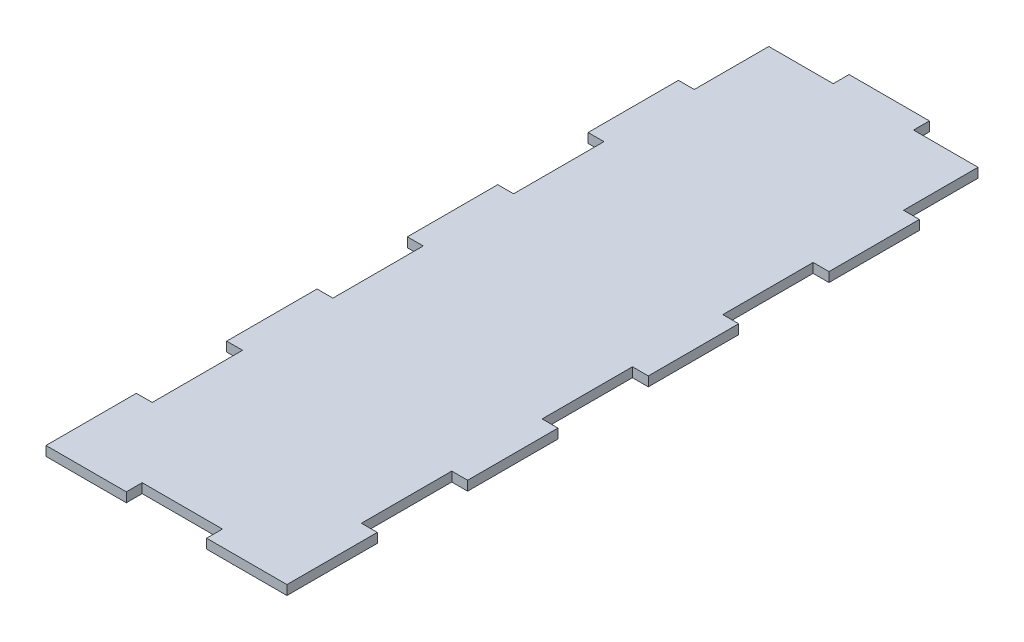
SolidWorks part; units mm, degrees
ref_plane "Front Plane" through (0, 0, 0) normal (0, 0, 1) x (1, 0, 0)
ref_plane "Top Plane" through (0, 0, 0) normal (0, 1, 0) x (1, 0, 0)
ref_plane "Right Plane" through (0, 0, 0) normal (1, 0, 0) x (0, 0, -1)
sketch "Sketch1" plane through (0, 0, 0) normal (0, 1, 0) x (1, 0, 0)
  line L0 (-38, -114) -> (-12.6667, -114)
  line L1 (-38, -114) -> (38, -114) construction
  line L2 (-38, -114) -> (-38, 114) construction
  line L3 (-38, 114) -> (38, 114) construction
  line L4 (38, -114) -> (38, 114) construction
  line L5 (0, 114) -> (0, -114) construction
  line L6 (-38, 0) -> (38, 0) construction
  line L7 (-12.6667, -114) -> (-12.6667, -109)
  line L8 (-12.6667, -109) -> (0, -109)
  line L9 (-38, -114) -> (-38, -85.5)
  line L13 (-38, -85.5) -> (-33, -85.5)
  line L14 (-33, -85.5) -> (-33, -57)
  line L15 (-33, -57) -> (-38, -57)
  line L20 (0, -109) -> (0, 114)
  line L22 (-33, 109) -> (-33, 85.5)
  line L23 (-33, 109) -> (-12.6667, 109)
  line L24 (-38, -57) -> (-38, -28.5)
  line L25 (-38, -28.5) -> (-33, -28.5)
  line L26 (-33, -28.5) -> (-33, 0)
  line L27 (-33, 0) -> (-38, 0)
  line L28 (-38, 0) -> (-38, 28.5)
  line L29 (-38, 28.5) -> (-33, 28.5)
  line L30 (-33, 28.5) -> (-33, 57)
  line L31 (-33, 57) -> (-38, 57)
  line L32 (-38, 57) -> (-38, 85.5)
  line L33 (-38, 85.5) -> (-33, 85.5)
  line L34 (-12.6667, 109) -> (-12.6667, 114)
  line L35 (-12.6667, 114) -> (0, 114)
  point P56 (0, 0)
  dimension "D1" = 228
  dimension "D2" = 76
  dimension "D4" = 5
  dimension "D6" = 5
  dimension "D5" = 28.5
  dimension "D8" = 28.5
  dimension "D9" = 28.5
  dimension "D10" = 28.5
  dimension "D11" = 28.5
  dimension "D12" = 28.5
  dimension "D3" = 12.6667
  dimension "D7" = 5
  dimension "D13" = 28.5
extrude "Boss-Extrude1" add sketch "Sketch1" along normal blind 3
mirror "Mirror1" about plane through (0, 3, 109) normal (-1, 0, 0) of "Boss-Extrude1"
equation "\"3mm akryyli\"= 3mm"
equation "\"5mm akryyli\"= 5mm"
equation "\"D4@Sketch1\"=\"5mm akryyli\""
equation "\"D6@Sketch1\"=\"5mm akryyli\""
equation "\"D7@Sketch1\"=\"5mm akryyli\""
